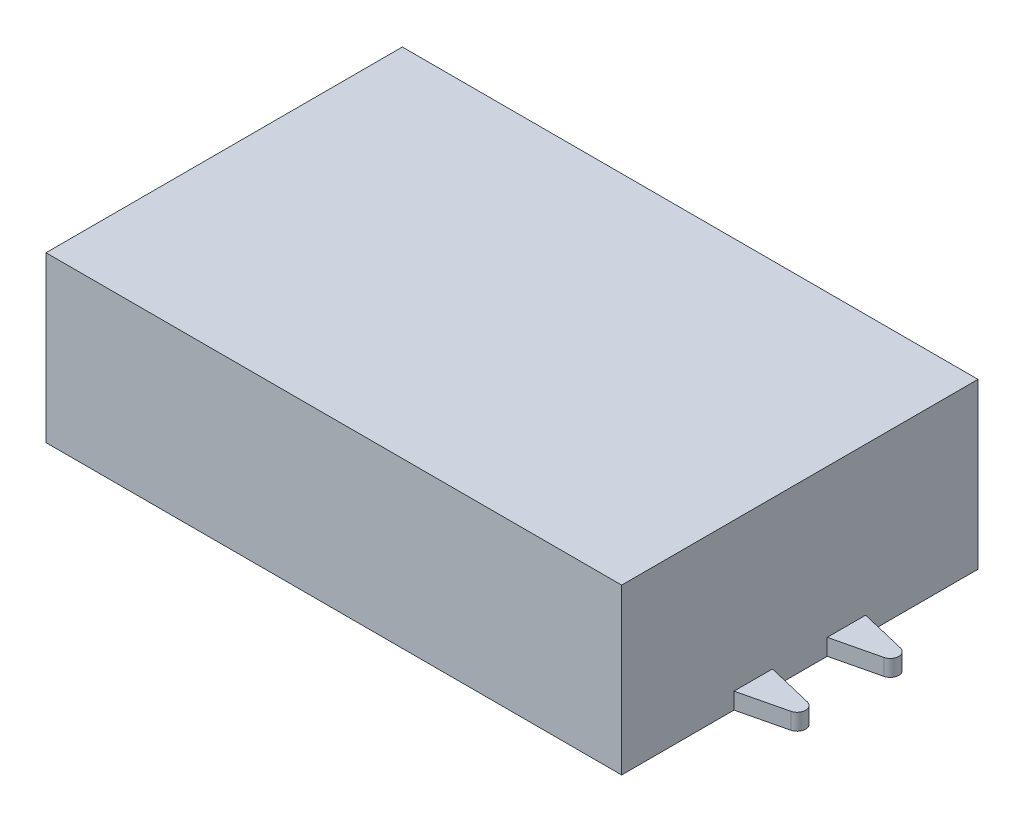
SolidWorks part; units mm, degrees
ref_plane "Front Plane" through (0, 0, 0) normal (0, 0, 1) x (1, 0, 0)
ref_plane "Top Plane" through (0, 0, 0) normal (0, 1, 0) x (1, 0, 0)
ref_plane "Right Plane" through (0, 0, 0) normal (1, 0, 0) x (0, 0, -1)
sketch "Sketch1" plane through (0, 0, 0) normal (0, 1, 0) x (1, 0, 0)
  line L1 (-52.5, -32.5) -> (52.5, -32.5)
  line L2 (-52.5, -32.5) -> (-52.5, 32.5)
  line L3 (-52.5, 32.5) -> (52.5, 32.5)
  line L4 (52.5, -32.5) -> (52.5, 32.5)
  line L5 (-52.5, -32.5) -> (52.5, 32.5) construction
  line L6 (-52.5, 32.5) -> (52.5, -32.5) construction
  point P0 (0, 0)
  dimension "D1" = 105
  dimension "D2" = 65
extrude "Boss-Extrude1" add sketch "Sketch1" along normal blind 30
sketch "Sketch3" plane through (0, 0, 0) normal (0, -1, 0) x (1, 0, 0)
  line L0 (52.5, 12) -> (60.8589, 10)
  line L1 (52.5, 32.5) -> (52.5, -32.5) construction
  line L2 (60.8589, 7) -> (52.5, 5)
  line L3 (52.5, 12) -> (52.5, 5)
  arc A0 (60.8589, 10) -> (60.8589, 7) centre (60.5, 8.5) cw
  point P6 (0, 0)
  point P8 (57.5, 7.5)
  dimension "D1" = 7
  dimension "D2" = 8
  dimension "D3" = 5
  dimension "D4" = 3
extrude "Boss-Extrude2" add sketch "Sketch3" against normal blind 3
mirror "Mirror1" about plane through (0, 0, 0) normal (0, 0, 1) of "Boss-Extrude2"
mirror "Mirror2" about plane through (0, 0, 0) normal (1, 0, 0) of "Mirror1", "Boss-Extrude2"
